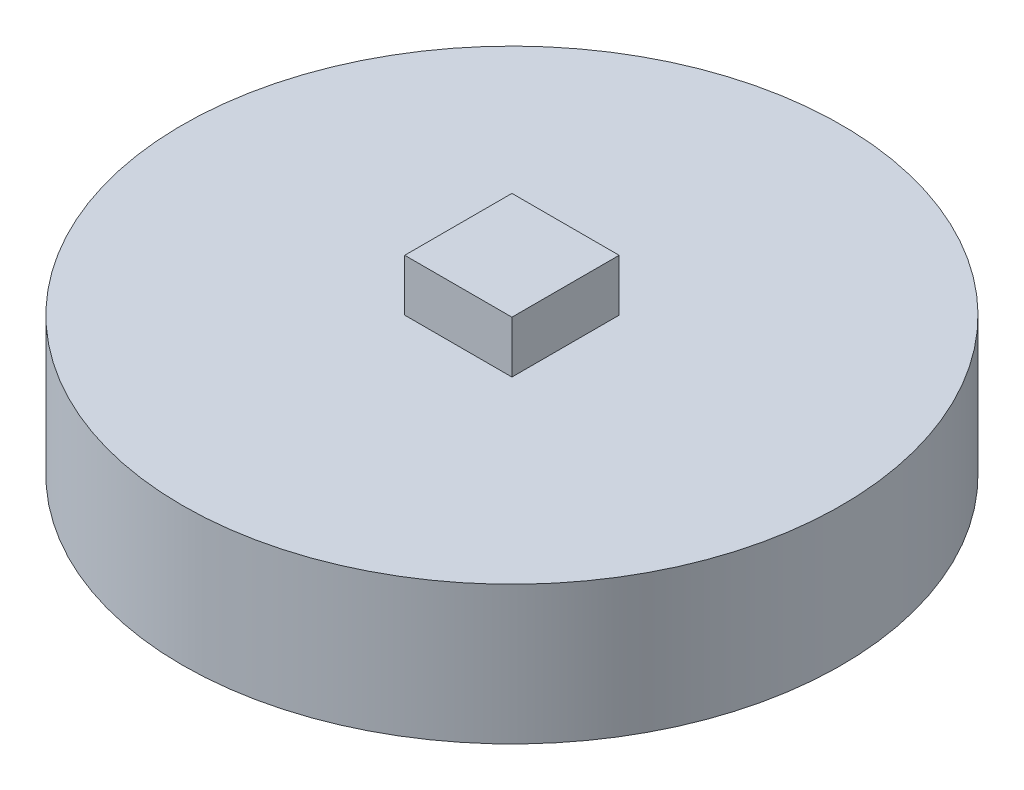
SolidWorks part; units mm, degrees
ref_plane "Plan de face" through (0, 0, 0) normal (0, 0, 1) x (1, 0, 0)
ref_plane "Plan de dessus" through (0, 0, 0) normal (0, 1, 0) x (1, 0, 0)
ref_plane "Plan de droite" through (0, 0, 0) normal (1, 0, 0) x (0, 0, -1)
sketch "Esquisse1" plane through (0, 0, 0) normal (0, 1, 0) x (1, 0, 0)
  circle A0 centre (0, 0) radius 19.06
  dimension "D1" = 38.12
extrude "Boss.-Extru.1" add sketch "Esquisse1" along normal blind 8
sketch "Esquisse2" plane through (0, 8, 0) normal (0, 1, 0) x (1, 0, 0)
  line L0 (0, 0) -> (0, 3.1) construction
  line L1 (0, 3.1) -> (3.1, 3.1)
  line L2 (3.1, 3.1) -> (3.1, -3.1)
  line L3 (3.1, -3.1) -> (-3.1, -3.1)
  line L4 (-3.1, -3.1) -> (-3.1, 3.1)
  line L5 (-3.1, 3.1) -> (0, 3.1)
  line L6 (0, 0) -> (3.1, 0) construction
  dimension "D1" = 6.2
  dimension "D2" = 6.2
  dimension "D3" = 3.1
  dimension "D4" = 3.1
extrude "Boss.-Extru.2" add sketch "Esquisse2" along normal blind 3
